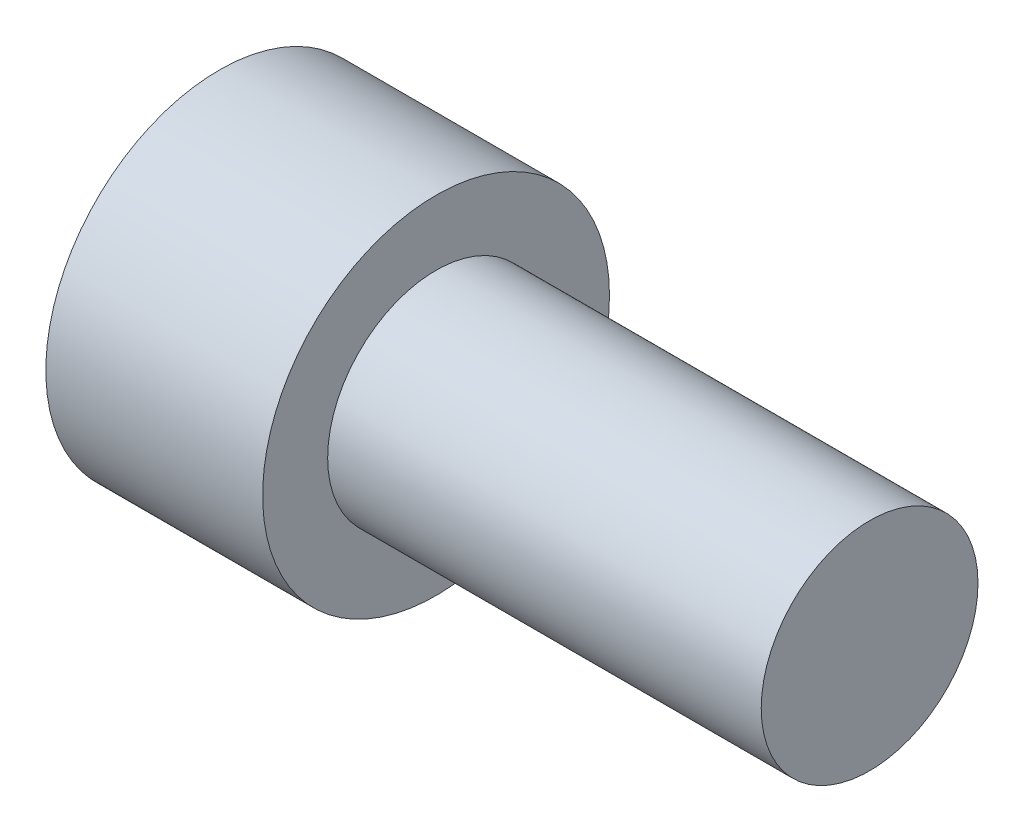
SolidWorks part; units mm, degrees
material "AISI 304"
ref_plane "前视基准面" through (0, 0, 0) normal (0, 0, 1) x (1, 0, 0)
ref_plane "上视基准面" through (0, 0, 0) normal (0, 1, 0) x (1, 0, 0)
ref_plane "右视基准面" through (0, 0, 0) normal (1, 0, 0) x (0, 0, -1)
sketch "草图1" plane through (0, 0, 0) normal (1, 0, 0) x (0, 0, -1)
  circle A0 centre (0, 0) radius 8
extrude "凸台-拉伸1" add sketch "草图1" along normal blind 10
sketch "草图2" plane through (10, 0, 0) normal (1, 0, 0) x (0, 0, -1)
  circle A0 centre (0, 0) radius 5
extrude "凸台-拉伸2" add sketch "草图2" along normal blind 20
